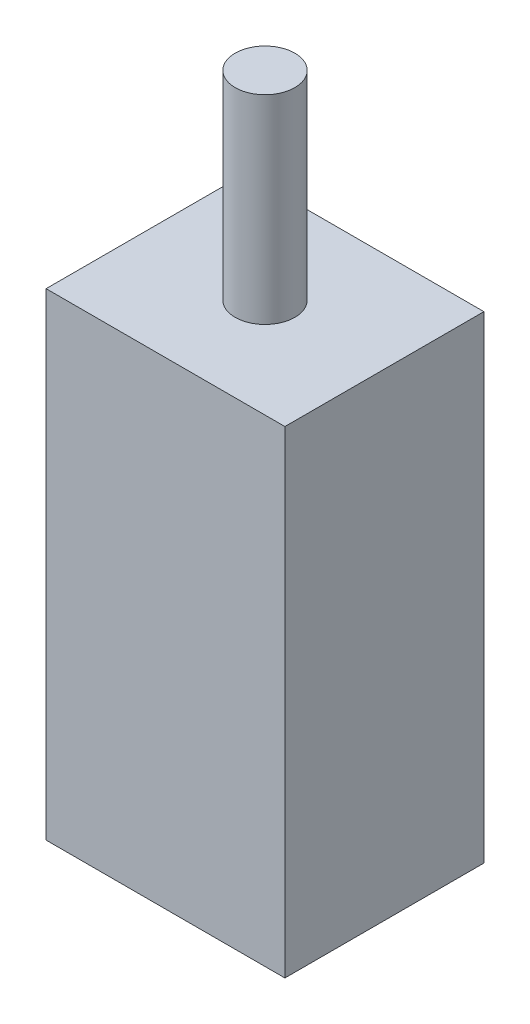
SolidWorks part; units mm, degrees
ref_plane "Front Plane" through (0, 0, 0) normal (1, 0, 0) x (0, 1, 0)
ref_plane "Top Plane" through (0, 0, 0) normal (0, 0, 1) x (0, 1, 0)
ref_plane "Right Plane" through (0, 0, 0) normal (0, 1, 0) x (-1, 0, 0)
sketch "Sketch1" plane through (0, 0, 0) normal (0, 0, 1) x (0, 1, 0)
  line L1 (-12, -6) -> (12, -6)
  line L2 (-12, -6) -> (-12, 6)
  line L3 (-12, 6) -> (12, 6)
  line L4 (12, -6) -> (12, 6)
  line L5 (-12, -6) -> (12, 6) construction
  line L6 (-12, 6) -> (12, -6) construction
  point P0 (0, 0)
  dimension "D1" = 24
  dimension "D2" = 12
extrude "Boss-Extrude1" add sketch "Sketch1" along normal mid plane 10
sketch "Sketch2" plane through (0, 12, 0) normal (0, 1, 0) x (-1, 0, 0)
  circle A0 centre (0, 0) radius 1.5
  dimension "D1" = 3
extrude "Boss-Extrude2" add sketch "Sketch2" along normal blind 10
sketch "Sketch3" plane through (0, -12, 0) normal (0, -1, 0) x (1, 0, 0)
  line L0 (0, 0) -> (4.1, 0) construction
  line L1 (4.2, 0.5) -> (4, 0.5)
  line L2 (4.2, 0.5) -> (4.2, -0.5)
  line L3 (4.2, -0.5) -> (4, -0.5)
  line L4 (4, 0.5) -> (4, -0.5)
  line L5 (4.2, 0.5) -> (4, -0.5) construction
  line L6 (4.2, -0.5) -> (4, 0.5) construction
  line L7 (0, -5.5) -> (0, 5.5) construction
  line L8 (-4, 0.5) -> (-4, -0.5)
  line L9 (-4.2, -0.5) -> (-4, -0.5)
  line L10 (-4.2, 0.5) -> (-4.2, -0.5)
  line L11 (-4.2, 0.5) -> (-4, 0.5)
  point P0 (4.1, 0)
  dimension "D1" = 4
  dimension "D2" = 0.2
  dimension "D3" = 1
extrude "Boss-Extrude3" add sketch "Sketch3" along normal blind 1
